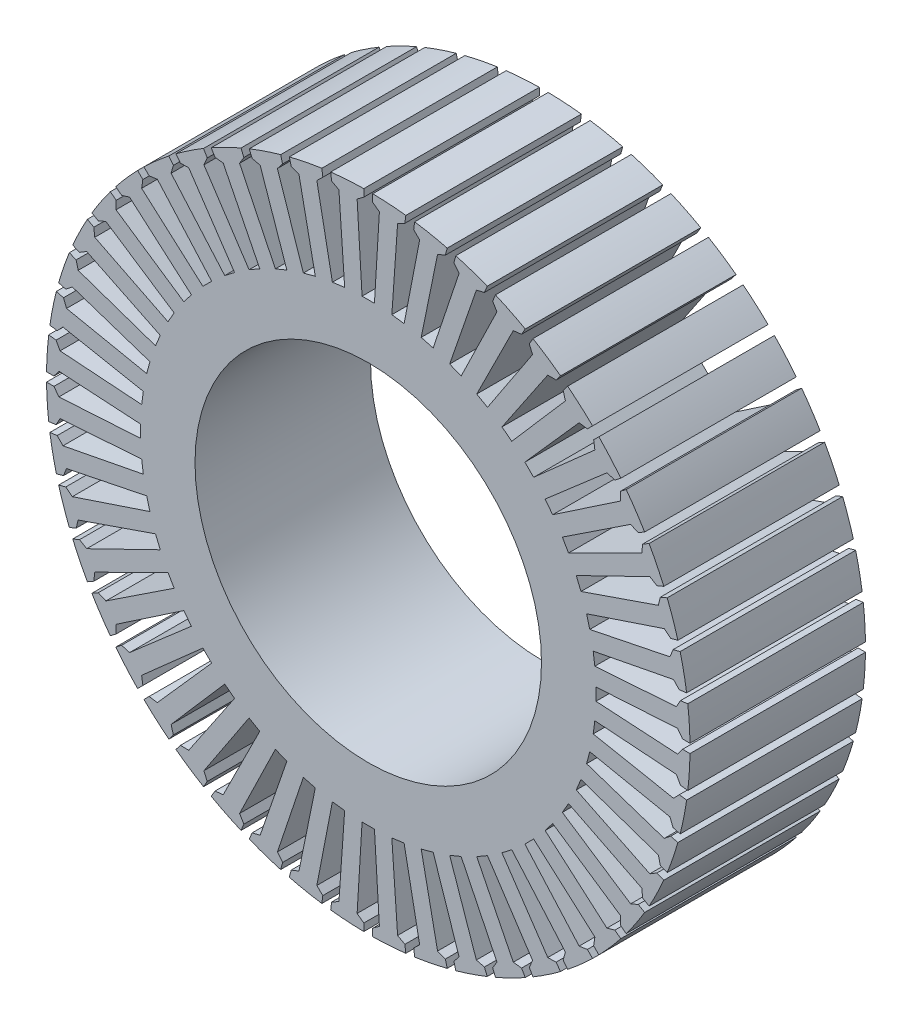
SolidWorks part; units mm, degrees
ref_plane "Спереди" through (0, 0, 0) normal (0, 0, 1) x (1, 0, 0)
ref_plane "Сверху" through (0, 0, 0) normal (0, 1, 0) x (1, 0, 0)
ref_plane "Справа" through (0, 0, 0) normal (1, 0, 0) x (0, 0, -1)
sketch "Эскиз1" plane through (0, 0, 0) normal (0, 0, 1) x (1, 0, 0)
  circle A0 centre (0, 0) radius 55
  circle A1 centre (0, 0) radius 29.6154
extrude "Stator_stack" add sketch "Эскиз1" along normal blind 30 from offset 15
sketch "Эскиз2" plane through (0, 0, 0) normal (0, 0, 1) x (1, 0, 0)
  line L0 (55.9948, -0.7615) -> (53.7308, -0.7615)
  line L1 (53.7308, -0.7615) -> (52.8846, -1.9038)
  line L2 (52.8846, -1.9038) -> (38.9231, -1.0577)
  line L3 (38.9231, -1.0577) -> (38.9231, 1.0577)
  line L4 (38.9231, 1.0577) -> (52.8846, 1.9038)
  line L5 (52.8846, 1.9038) -> (53.7308, 0.7615)
  line L6 (53.7308, 0.7615) -> (55.9948, 0.7615)
  line L7 (55.9948, 0.7615) -> (55.9948, -0.7615)
  line L8 (55.6152, 6.5538) -> (53.3705, 6.2582)
  line L9 (53.3705, 6.2582) -> (52.6807, 5.0153)
  line L10 (52.6807, 5.0153) -> (38.7281, 4.0318)
  line L11 (38.7281, 4.0318) -> (38.452, 6.1291)
  line L12 (38.452, 6.1291) -> (52.1837, 8.7904)
  line L13 (52.1837, 8.7904) -> (53.1717, 7.7683)
  line L14 (53.1717, 7.7683) -> (55.4164, 8.0638)
  line L15 (55.4164, 8.0638) -> (55.6152, 6.5538)
  line L16 (54.2839, 13.7569) -> (52.097, 13.171)
  line L17 (52.097, 13.171) -> (51.5754, 11.8486)
  line L18 (51.5754, 11.8486) -> (37.8706, 9.0524)
  line L19 (37.8706, 9.0524) -> (37.3231, 11.0957)
  line L20 (37.3231, 11.0957) -> (50.5899, 15.5265)
  line L21 (50.5899, 15.5265) -> (51.7028, 14.6421)
  line L22 (51.7028, 14.6421) -> (53.8897, 15.2281)
  line L23 (53.8897, 15.2281) -> (54.2839, 13.7569)
  line L24 (52.0239, 20.7247) -> (49.9322, 19.8583)
  line L25 (49.9322, 19.8583) -> (49.5876, 18.4791)
  line L26 (49.5876, 18.4791) -> (36.365, 13.918)
  line L27 (36.365, 13.918) -> (35.5555, 15.8724)
  line L28 (35.5555, 15.8724) -> (48.1304, 21.997)
  line L29 (48.1304, 21.997) -> (49.3493, 21.2654)
  line L30 (49.3493, 21.2654) -> (51.441, 22.1319)
  line L31 (51.441, 22.1319) -> (52.0239, 20.7247)
  line L32 (48.8737, 27.3379) -> (46.913, 26.2059)
  line L33 (46.913, 26.2059) -> (46.7513, 24.7935)
  line L34 (46.7513, 24.7935) -> (34.2372, 18.5456)
  line L35 (34.2372, 18.5456) -> (33.1795, 20.3775)
  line L36 (33.1795, 20.3775) -> (44.8475, 28.0911)
  line L37 (44.8475, 28.0911) -> (46.1514, 27.5249)
  line L38 (46.1514, 27.5249) -> (48.1122, 28.6569)
  line L39 (48.1122, 28.6569) -> (48.8737, 27.3379)
  line L40 (44.8873, 33.4833) -> (43.0911, 32.1051)
  line L41 (43.0911, 32.1051) -> (43.1152, 30.6837)
  line L42 (43.1152, 30.6837) -> (31.5236, 22.8557)
  line L43 (31.5236, 22.8557) -> (30.2359, 24.534)
  line L44 (30.2359, 24.534) -> (40.7972, 33.7045)
  line L45 (40.7972, 33.7045) -> (42.1639, 33.3134)
  line L46 (42.1639, 33.3134) -> (43.9601, 34.6917)
  line L47 (43.9601, 34.6917) -> (44.8873, 33.4833)
  line L48 (40.1328, 39.0558) -> (38.5319, 37.4549)
  line L49 (38.5319, 37.4549) -> (38.7413, 36.0488)
  line L50 (38.7413, 36.0488) -> (28.2707, 26.7749)
  line L51 (28.2707, 26.7749) -> (26.7749, 28.2707)
  line L52 (26.7749, 28.2707) -> (36.0488, 38.7413)
  line L53 (36.0488, 38.7413) -> (37.4549, 38.5319)
  line L54 (37.4549, 38.5319) -> (39.0558, 40.1328)
  line L55 (39.0558, 40.1328) -> (40.1328, 39.0558)
  line L56 (34.6917, 43.9601) -> (33.3134, 42.1639)
  line L57 (33.3134, 42.1639) -> (33.7045, 40.7972)
  line L58 (33.7045, 40.7972) -> (24.534, 30.2359)
  line L59 (24.534, 30.2359) -> (22.8557, 31.5236)
  line L60 (22.8557, 31.5236) -> (30.6837, 43.1152)
  line L61 (30.6837, 43.1152) -> (32.1051, 43.0911)
  line L62 (32.1051, 43.0911) -> (33.4833, 44.8873)
  line L63 (33.4833, 44.8873) -> (34.6917, 43.9601)
  line L64 (28.6569, 48.1122) -> (27.5249, 46.1514)
  line L65 (27.5249, 46.1514) -> (28.0911, 44.8475)
  line L66 (28.0911, 44.8475) -> (20.3775, 33.1795)
  line L67 (20.3775, 33.1795) -> (18.5456, 34.2372)
  line L68 (18.5456, 34.2372) -> (24.7935, 46.7513)
  line L69 (24.7935, 46.7513) -> (26.2059, 46.913)
  line L70 (26.2059, 46.913) -> (27.3379, 48.8737)
  line L71 (27.3379, 48.8737) -> (28.6569, 48.1122)
  line L72 (22.1319, 51.441) -> (21.2654, 49.3493)
  line L73 (21.2654, 49.3493) -> (21.997, 48.1304)
  line L74 (21.997, 48.1304) -> (15.8724, 35.5555)
  line L75 (15.8724, 35.5555) -> (13.918, 36.365)
  line L76 (13.918, 36.365) -> (18.4791, 49.5876)
  line L77 (18.4791, 49.5876) -> (19.8583, 49.9322)
  line L78 (19.8583, 49.9322) -> (20.7247, 52.0239)
  line L79 (20.7247, 52.0239) -> (22.1319, 51.441)
  line L80 (15.2281, 53.8897) -> (14.6421, 51.7028)
  line L81 (14.6421, 51.7028) -> (15.5265, 50.5899)
  line L82 (15.5265, 50.5899) -> (11.0957, 37.3231)
  line L83 (11.0957, 37.3231) -> (9.0524, 37.8706)
  line L84 (9.0524, 37.8706) -> (11.8486, 51.5754)
  line L85 (11.8486, 51.5754) -> (13.171, 52.097)
  line L86 (13.171, 52.097) -> (13.7569, 54.2839)
  line L87 (13.7569, 54.2839) -> (15.2281, 53.8897)
  line L88 (8.0638, 55.4164) -> (7.7683, 53.1717)
  line L89 (7.7683, 53.1717) -> (8.7904, 52.1837)
  line L90 (8.7904, 52.1837) -> (6.1291, 38.452)
  line L91 (6.1291, 38.452) -> (4.0318, 38.7281)
  line L92 (4.0318, 38.7281) -> (5.0153, 52.6807)
  line L93 (5.0153, 52.6807) -> (6.2582, 53.3705)
  line L94 (6.2582, 53.3705) -> (6.5538, 55.6152)
  line L95 (6.5538, 55.6152) -> (8.0638, 55.4164)
  line L96 (0.7615, 55.9948) -> (0.7615, 53.7308)
  line L97 (0.7615, 53.7308) -> (1.9038, 52.8846)
  line L98 (1.9038, 52.8846) -> (1.0577, 38.9231)
  line L99 (1.0577, 38.9231) -> (-1.0577, 38.9231)
  line L100 (-1.0577, 38.9231) -> (-1.9038, 52.8846)
  line L101 (-1.9038, 52.8846) -> (-0.7615, 53.7308)
  line L102 (-0.7615, 53.7308) -> (-0.7615, 55.9948)
  line L103 (-0.7615, 55.9948) -> (0.7615, 55.9948)
  line L104 (-6.5538, 55.6152) -> (-6.2582, 53.3705)
  line L105 (-6.2582, 53.3705) -> (-5.0153, 52.6807)
  line L106 (-5.0153, 52.6807) -> (-4.0318, 38.7281)
  line L107 (-4.0318, 38.7281) -> (-6.1291, 38.452)
  line L108 (-6.1291, 38.452) -> (-8.7904, 52.1837)
  line L109 (-8.7904, 52.1837) -> (-7.7683, 53.1717)
  line L110 (-7.7683, 53.1717) -> (-8.0638, 55.4164)
  line L111 (-8.0638, 55.4164) -> (-6.5538, 55.6152)
  line L112 (-13.7569, 54.2839) -> (-13.171, 52.097)
  line L113 (-13.171, 52.097) -> (-11.8486, 51.5754)
  line L114 (-11.8486, 51.5754) -> (-9.0524, 37.8706)
  line L115 (-9.0524, 37.8706) -> (-11.0957, 37.3231)
  line L116 (-11.0957, 37.3231) -> (-15.5265, 50.5899)
  line L117 (-15.5265, 50.5899) -> (-14.6421, 51.7028)
  line L118 (-14.6421, 51.7028) -> (-15.2281, 53.8897)
  line L119 (-15.2281, 53.8897) -> (-13.7569, 54.2839)
  line L120 (-20.7247, 52.0239) -> (-19.8583, 49.9322)
  line L121 (-19.8583, 49.9322) -> (-18.4791, 49.5876)
  line L122 (-18.4791, 49.5876) -> (-13.918, 36.365)
  line L123 (-13.918, 36.365) -> (-15.8724, 35.5555)
  line L124 (-15.8724, 35.5555) -> (-21.997, 48.1304)
  line L125 (-21.997, 48.1304) -> (-21.2654, 49.3493)
  line L126 (-21.2654, 49.3493) -> (-22.1319, 51.441)
  line L127 (-22.1319, 51.441) -> (-20.7247, 52.0239)
  line L128 (-27.3379, 48.8737) -> (-26.2059, 46.913)
  line L129 (-26.2059, 46.913) -> (-24.7935, 46.7513)
  line L130 (-24.7935, 46.7513) -> (-18.5456, 34.2372)
  line L131 (-18.5456, 34.2372) -> (-20.3775, 33.1795)
  line L132 (-20.3775, 33.1795) -> (-28.0911, 44.8475)
  line L133 (-28.0911, 44.8475) -> (-27.5249, 46.1514)
  line L134 (-27.5249, 46.1514) -> (-28.6569, 48.1122)
  line L135 (-28.6569, 48.1122) -> (-27.3379, 48.8737)
  line L136 (-33.4833, 44.8873) -> (-32.1051, 43.0911)
  line L137 (-32.1051, 43.0911) -> (-30.6837, 43.1152)
  line L138 (-30.6837, 43.1152) -> (-22.8557, 31.5236)
  line L139 (-22.8557, 31.5236) -> (-24.534, 30.2359)
  line L140 (-24.534, 30.2359) -> (-33.7045, 40.7972)
  line L141 (-33.7045, 40.7972) -> (-33.3134, 42.1639)
  line L142 (-33.3134, 42.1639) -> (-34.6917, 43.9601)
  line L143 (-34.6917, 43.9601) -> (-33.4833, 44.8873)
  line L144 (-39.0558, 40.1328) -> (-37.4549, 38.5319)
  line L145 (-37.4549, 38.5319) -> (-36.0488, 38.7413)
  line L146 (-36.0488, 38.7413) -> (-26.7749, 28.2707)
  line L147 (-26.7749, 28.2707) -> (-28.2707, 26.7749)
  line L148 (-28.2707, 26.7749) -> (-38.7413, 36.0488)
  line L149 (-38.7413, 36.0488) -> (-38.5319, 37.4549)
  line L150 (-38.5319, 37.4549) -> (-40.1328, 39.0558)
  line L151 (-40.1328, 39.0558) -> (-39.0558, 40.1328)
  line L152 (-43.9601, 34.6917) -> (-42.1639, 33.3134)
  line L153 (-42.1639, 33.3134) -> (-40.7972, 33.7045)
  line L154 (-40.7972, 33.7045) -> (-30.2359, 24.534)
  line L155 (-30.2359, 24.534) -> (-31.5236, 22.8557)
  line L156 (-31.5236, 22.8557) -> (-43.1152, 30.6837)
  line L157 (-43.1152, 30.6837) -> (-43.0911, 32.1051)
  line L158 (-43.0911, 32.1051) -> (-44.8873, 33.4833)
  line L159 (-44.8873, 33.4833) -> (-43.9601, 34.6917)
  line L160 (-48.1122, 28.6569) -> (-46.1514, 27.5249)
  line L161 (-46.1514, 27.5249) -> (-44.8475, 28.0911)
  line L162 (-44.8475, 28.0911) -> (-33.1795, 20.3775)
  line L163 (-33.1795, 20.3775) -> (-34.2372, 18.5456)
  line L164 (-34.2372, 18.5456) -> (-46.7513, 24.7935)
  line L165 (-46.7513, 24.7935) -> (-46.913, 26.2059)
  line L166 (-46.913, 26.2059) -> (-48.8737, 27.3379)
  line L167 (-48.8737, 27.3379) -> (-48.1122, 28.6569)
  line L168 (-51.441, 22.1319) -> (-49.3493, 21.2654)
  line L169 (-49.3493, 21.2654) -> (-48.1304, 21.997)
  line L170 (-48.1304, 21.997) -> (-35.5555, 15.8724)
  line L171 (-35.5555, 15.8724) -> (-36.365, 13.918)
  line L172 (-36.365, 13.918) -> (-49.5876, 18.4791)
  line L173 (-49.5876, 18.4791) -> (-49.9322, 19.8583)
  line L174 (-49.9322, 19.8583) -> (-52.0239, 20.7247)
  line L175 (-52.0239, 20.7247) -> (-51.441, 22.1319)
  line L176 (-53.8897, 15.2281) -> (-51.7028, 14.6421)
  line L177 (-51.7028, 14.6421) -> (-50.5899, 15.5265)
  line L178 (-50.5899, 15.5265) -> (-37.3231, 11.0957)
  line L179 (-37.3231, 11.0957) -> (-37.8706, 9.0524)
  line L180 (-37.8706, 9.0524) -> (-51.5754, 11.8486)
  line L181 (-51.5754, 11.8486) -> (-52.097, 13.171)
  line L182 (-52.097, 13.171) -> (-54.2839, 13.7569)
  line L183 (-54.2839, 13.7569) -> (-53.8897, 15.2281)
  line L184 (-55.4164, 8.0638) -> (-53.1717, 7.7683)
  line L185 (-53.1717, 7.7683) -> (-52.1837, 8.7904)
  line L186 (-52.1837, 8.7904) -> (-38.452, 6.1291)
  line L187 (-38.452, 6.1291) -> (-38.7281, 4.0318)
  line L188 (-38.7281, 4.0318) -> (-52.6807, 5.0153)
  line L189 (-52.6807, 5.0153) -> (-53.3705, 6.2582)
  line L190 (-53.3705, 6.2582) -> (-55.6152, 6.5538)
  line L191 (-55.6152, 6.5538) -> (-55.4164, 8.0638)
  line L192 (-55.9948, 0.7615) -> (-53.7308, 0.7615)
  line L193 (-53.7308, 0.7615) -> (-52.8846, 1.9038)
  line L194 (-52.8846, 1.9038) -> (-38.9231, 1.0577)
  line L195 (-38.9231, 1.0577) -> (-38.9231, -1.0577)
  line L196 (-38.9231, -1.0577) -> (-52.8846, -1.9038)
  line L197 (-52.8846, -1.9038) -> (-53.7308, -0.7615)
  line L198 (-53.7308, -0.7615) -> (-55.9948, -0.7615)
  line L199 (-55.9948, -0.7615) -> (-55.9948, 0.7615)
  line L200 (-55.6152, -6.5538) -> (-53.3705, -6.2582)
  line L201 (-53.3705, -6.2582) -> (-52.6807, -5.0153)
  line L202 (-52.6807, -5.0153) -> (-38.7281, -4.0318)
  line L203 (-38.7281, -4.0318) -> (-38.452, -6.1291)
  line L204 (-38.452, -6.1291) -> (-52.1837, -8.7904)
  line L205 (-52.1837, -8.7904) -> (-53.1717, -7.7683)
  line L206 (-53.1717, -7.7683) -> (-55.4164, -8.0638)
  line L207 (-55.4164, -8.0638) -> (-55.6152, -6.5538)
  line L208 (-54.2839, -13.7569) -> (-52.097, -13.171)
  line L209 (-52.097, -13.171) -> (-51.5754, -11.8486)
  line L210 (-51.5754, -11.8486) -> (-37.8706, -9.0524)
  line L211 (-37.8706, -9.0524) -> (-37.3231, -11.0957)
  line L212 (-37.3231, -11.0957) -> (-50.5899, -15.5265)
  line L213 (-50.5899, -15.5265) -> (-51.7028, -14.6421)
  line L214 (-51.7028, -14.6421) -> (-53.8897, -15.2281)
  line L215 (-53.8897, -15.2281) -> (-54.2839, -13.7569)
  line L216 (-52.0239, -20.7247) -> (-49.9322, -19.8583)
  line L217 (-49.9322, -19.8583) -> (-49.5876, -18.4791)
  line L218 (-49.5876, -18.4791) -> (-36.365, -13.918)
  line L219 (-36.365, -13.918) -> (-35.5555, -15.8724)
  line L220 (-35.5555, -15.8724) -> (-48.1304, -21.997)
  line L221 (-48.1304, -21.997) -> (-49.3493, -21.2654)
  line L222 (-49.3493, -21.2654) -> (-51.441, -22.1319)
  line L223 (-51.441, -22.1319) -> (-52.0239, -20.7247)
  line L224 (-48.8737, -27.3379) -> (-46.913, -26.2059)
  line L225 (-46.913, -26.2059) -> (-46.7513, -24.7935)
  line L226 (-46.7513, -24.7935) -> (-34.2372, -18.5456)
  line L227 (-34.2372, -18.5456) -> (-33.1795, -20.3775)
  line L228 (-33.1795, -20.3775) -> (-44.8475, -28.0911)
  line L229 (-44.8475, -28.0911) -> (-46.1514, -27.5249)
  line L230 (-46.1514, -27.5249) -> (-48.1122, -28.6569)
  line L231 (-48.1122, -28.6569) -> (-48.8737, -27.3379)
  line L232 (-44.8873, -33.4833) -> (-43.0911, -32.1051)
  line L233 (-43.0911, -32.1051) -> (-43.1152, -30.6837)
  line L234 (-43.1152, -30.6837) -> (-31.5236, -22.8557)
  line L235 (-31.5236, -22.8557) -> (-30.2359, -24.534)
  line L236 (-30.2359, -24.534) -> (-40.7972, -33.7045)
  line L237 (-40.7972, -33.7045) -> (-42.1639, -33.3134)
  line L238 (-42.1639, -33.3134) -> (-43.9601, -34.6917)
  line L239 (-43.9601, -34.6917) -> (-44.8873, -33.4833)
  line L240 (-40.1328, -39.0558) -> (-38.5319, -37.4549)
  line L241 (-38.5319, -37.4549) -> (-38.7413, -36.0488)
  line L242 (-38.7413, -36.0488) -> (-28.2707, -26.7749)
  line L243 (-28.2707, -26.7749) -> (-26.7749, -28.2707)
  line L244 (-26.7749, -28.2707) -> (-36.0488, -38.7413)
  line L245 (-36.0488, -38.7413) -> (-37.4549, -38.5319)
  line L246 (-37.4549, -38.5319) -> (-39.0558, -40.1328)
  line L247 (-39.0558, -40.1328) -> (-40.1328, -39.0558)
  line L248 (-34.6917, -43.9601) -> (-33.3134, -42.1639)
  line L249 (-33.3134, -42.1639) -> (-33.7045, -40.7972)
  line L250 (-33.7045, -40.7972) -> (-24.534, -30.2359)
  line L251 (-24.534, -30.2359) -> (-22.8557, -31.5236)
  line L252 (-22.8557, -31.5236) -> (-30.6837, -43.1152)
  line L253 (-30.6837, -43.1152) -> (-32.1051, -43.0911)
  line L254 (-32.1051, -43.0911) -> (-33.4833, -44.8873)
  line L255 (-33.4833, -44.8873) -> (-34.6917, -43.9601)
  line L256 (-28.6569, -48.1122) -> (-27.5249, -46.1514)
  line L257 (-27.5249, -46.1514) -> (-28.0911, -44.8475)
  line L258 (-28.0911, -44.8475) -> (-20.3775, -33.1795)
  line L259 (-20.3775, -33.1795) -> (-18.5456, -34.2372)
  line L260 (-18.5456, -34.2372) -> (-24.7935, -46.7513)
  line L261 (-24.7935, -46.7513) -> (-26.2059, -46.913)
  line L262 (-26.2059, -46.913) -> (-27.3379, -48.8737)
  line L263 (-27.3379, -48.8737) -> (-28.6569, -48.1122)
  line L264 (-22.1319, -51.441) -> (-21.2654, -49.3493)
  line L265 (-21.2654, -49.3493) -> (-21.997, -48.1304)
  line L266 (-21.997, -48.1304) -> (-15.8724, -35.5555)
  line L267 (-15.8724, -35.5555) -> (-13.918, -36.365)
  line L268 (-13.918, -36.365) -> (-18.4791, -49.5876)
  line L269 (-18.4791, -49.5876) -> (-19.8583, -49.9322)
  line L270 (-19.8583, -49.9322) -> (-20.7247, -52.0239)
  line L271 (-20.7247, -52.0239) -> (-22.1319, -51.441)
  line L272 (-15.2281, -53.8897) -> (-14.6421, -51.7028)
  line L273 (-14.6421, -51.7028) -> (-15.5265, -50.5899)
  line L274 (-15.5265, -50.5899) -> (-11.0957, -37.3231)
  line L275 (-11.0957, -37.3231) -> (-9.0524, -37.8706)
  line L276 (-9.0524, -37.8706) -> (-11.8486, -51.5754)
  line L277 (-11.8486, -51.5754) -> (-13.171, -52.097)
  line L278 (-13.171, -52.097) -> (-13.7569, -54.2839)
  line L279 (-13.7569, -54.2839) -> (-15.2281, -53.8897)
  line L280 (-8.0638, -55.4164) -> (-7.7683, -53.1717)
  line L281 (-7.7683, -53.1717) -> (-8.7904, -52.1837)
  line L282 (-8.7904, -52.1837) -> (-6.1291, -38.452)
  line L283 (-6.1291, -38.452) -> (-4.0318, -38.7281)
  line L284 (-4.0318, -38.7281) -> (-5.0153, -52.6807)
  line L285 (-5.0153, -52.6807) -> (-6.2582, -53.3705)
  line L286 (-6.2582, -53.3705) -> (-6.5538, -55.6152)
  line L287 (-6.5538, -55.6152) -> (-8.0638, -55.4164)
  line L288 (-0.7615, -55.9948) -> (-0.7615, -53.7308)
  line L289 (-0.7615, -53.7308) -> (-1.9038, -52.8846)
  line L290 (-1.9038, -52.8846) -> (-1.0577, -38.9231)
  line L291 (-1.0577, -38.9231) -> (1.0577, -38.9231)
  line L292 (1.0577, -38.9231) -> (1.9038, -52.8846)
  line L293 (1.9038, -52.8846) -> (0.7615, -53.7308)
  line L294 (0.7615, -53.7308) -> (0.7615, -55.9948)
  line L295 (0.7615, -55.9948) -> (-0.7615, -55.9948)
  line L296 (6.5538, -55.6152) -> (6.2582, -53.3705)
  line L297 (6.2582, -53.3705) -> (5.0153, -52.6807)
  line L298 (5.0153, -52.6807) -> (4.0318, -38.7281)
  line L299 (4.0318, -38.7281) -> (6.1291, -38.452)
  line L300 (6.1291, -38.452) -> (8.7904, -52.1837)
  line L301 (8.7904, -52.1837) -> (7.7683, -53.1717)
  line L302 (7.7683, -53.1717) -> (8.0638, -55.4164)
  line L303 (8.0638, -55.4164) -> (6.5538, -55.6152)
  line L304 (13.7569, -54.2839) -> (13.171, -52.097)
  line L305 (13.171, -52.097) -> (11.8486, -51.5754)
  line L306 (11.8486, -51.5754) -> (9.0524, -37.8706)
  line L307 (9.0524, -37.8706) -> (11.0957, -37.3231)
  line L308 (11.0957, -37.3231) -> (15.5265, -50.5899)
  line L309 (15.5265, -50.5899) -> (14.6421, -51.7028)
  line L310 (14.6421, -51.7028) -> (15.2281, -53.8897)
  line L311 (15.2281, -53.8897) -> (13.7569, -54.2839)
  line L312 (20.7247, -52.0239) -> (19.8583, -49.9322)
  line L313 (19.8583, -49.9322) -> (18.4791, -49.5876)
  line L314 (18.4791, -49.5876) -> (13.918, -36.365)
  line L315 (13.918, -36.365) -> (15.8724, -35.5555)
  line L316 (15.8724, -35.5555) -> (21.997, -48.1304)
  line L317 (21.997, -48.1304) -> (21.2654, -49.3493)
  line L318 (21.2654, -49.3493) -> (22.1319, -51.441)
  line L319 (22.1319, -51.441) -> (20.7247, -52.0239)
  line L320 (27.3379, -48.8737) -> (26.2059, -46.913)
  line L321 (26.2059, -46.913) -> (24.7935, -46.7513)
  line L322 (24.7935, -46.7513) -> (18.5456, -34.2372)
  line L323 (18.5456, -34.2372) -> (20.3775, -33.1795)
  line L324 (20.3775, -33.1795) -> (28.0911, -44.8475)
  line L325 (28.0911, -44.8475) -> (27.5249, -46.1514)
  line L326 (27.5249, -46.1514) -> (28.6569, -48.1122)
  line L327 (28.6569, -48.1122) -> (27.3379, -48.8737)
  line L328 (33.4833, -44.8873) -> (32.1051, -43.0911)
  line L329 (32.1051, -43.0911) -> (30.6837, -43.1152)
  line L330 (30.6837, -43.1152) -> (22.8557, -31.5236)
  line L331 (22.8557, -31.5236) -> (24.534, -30.2359)
  line L332 (24.534, -30.2359) -> (33.7045, -40.7972)
  line L333 (33.7045, -40.7972) -> (33.3134, -42.1639)
  line L334 (33.3134, -42.1639) -> (34.6917, -43.9601)
  line L335 (34.6917, -43.9601) -> (33.4833, -44.8873)
  line L336 (39.0558, -40.1328) -> (37.4549, -38.5319)
  line L337 (37.4549, -38.5319) -> (36.0488, -38.7413)
  line L338 (36.0488, -38.7413) -> (26.7749, -28.2707)
  line L339 (26.7749, -28.2707) -> (28.2707, -26.7749)
  line L340 (28.2707, -26.7749) -> (38.7413, -36.0488)
  line L341 (38.7413, -36.0488) -> (38.5319, -37.4549)
  line L342 (38.5319, -37.4549) -> (40.1328, -39.0558)
  line L343 (40.1328, -39.0558) -> (39.0558, -40.1328)
  line L344 (43.9601, -34.6917) -> (42.1639, -33.3134)
  line L345 (42.1639, -33.3134) -> (40.7972, -33.7045)
  line L346 (40.7972, -33.7045) -> (30.2359, -24.534)
  line L347 (30.2359, -24.534) -> (31.5236, -22.8557)
  line L348 (31.5236, -22.8557) -> (43.1152, -30.6837)
  line L349 (43.1152, -30.6837) -> (43.0911, -32.1051)
  line L350 (43.0911, -32.1051) -> (44.8873, -33.4833)
  line L351 (44.8873, -33.4833) -> (43.9601, -34.6917)
  line L352 (48.1122, -28.6569) -> (46.1514, -27.5249)
  line L353 (46.1514, -27.5249) -> (44.8475, -28.0911)
  line L354 (44.8475, -28.0911) -> (33.1795, -20.3775)
  line L355 (33.1795, -20.3775) -> (34.2372, -18.5456)
  line L356 (34.2372, -18.5456) -> (46.7513, -24.7935)
  line L357 (46.7513, -24.7935) -> (46.913, -26.2059)
  line L358 (46.913, -26.2059) -> (48.8737, -27.3379)
  line L359 (48.8737, -27.3379) -> (48.1122, -28.6569)
  line L360 (51.441, -22.1319) -> (49.3493, -21.2654)
  line L361 (49.3493, -21.2654) -> (48.1304, -21.997)
  line L362 (48.1304, -21.997) -> (35.5555, -15.8724)
  line L363 (35.5555, -15.8724) -> (36.365, -13.918)
  line L364 (36.365, -13.918) -> (49.5876, -18.4791)
  line L365 (49.5876, -18.4791) -> (49.9322, -19.8583)
  line L366 (49.9322, -19.8583) -> (52.0239, -20.7247)
  line L367 (52.0239, -20.7247) -> (51.441, -22.1319)
  line L368 (53.8897, -15.2281) -> (51.7028, -14.6421)
  line L369 (51.7028, -14.6421) -> (50.5899, -15.5265)
  line L370 (50.5899, -15.5265) -> (37.3231, -11.0957)
  line L371 (37.3231, -11.0957) -> (37.8706, -9.0524)
  line L372 (37.8706, -9.0524) -> (51.5754, -11.8486)
  line L373 (51.5754, -11.8486) -> (52.097, -13.171)
  line L374 (52.097, -13.171) -> (54.2839, -13.7569)
  line L375 (54.2839, -13.7569) -> (53.8897, -15.2281)
  line L376 (55.4164, -8.0638) -> (53.1717, -7.7683)
  line L377 (53.1717, -7.7683) -> (52.1837, -8.7904)
  line L378 (52.1837, -8.7904) -> (38.452, -6.1291)
  line L379 (38.452, -6.1291) -> (38.7281, -4.0318)
  line L380 (38.7281, -4.0318) -> (52.6807, -5.0153)
  line L381 (52.6807, -5.0153) -> (53.3705, -6.2582)
  line L382 (53.3705, -6.2582) -> (55.6152, -6.5538)
  line L383 (55.6152, -6.5538) -> (55.4164, -8.0638)
extrude "Stator_48_slots" cut sketch "Эскиз2" against normal mid plane 32
